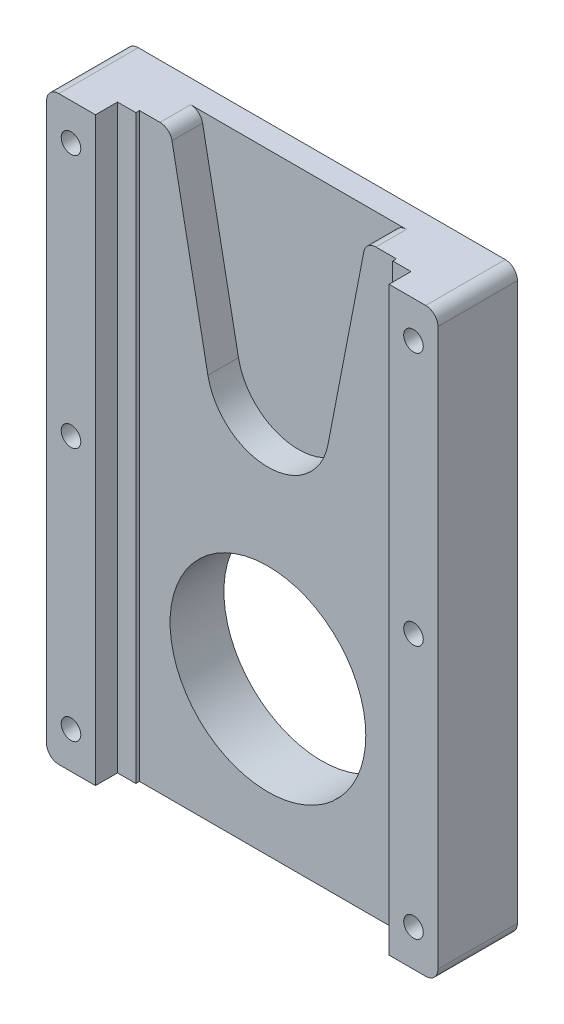
SolidWorks part; units mm, degrees
ref_plane "Plan de face" through (0, 0, 0) normal (0, 0, 1) x (1, 0, 0)
ref_plane "Plan de dessus" through (0, 0, 0) normal (0, 1, 0) x (1, 0, 0)
ref_plane "Plan de droite" through (0, 0, 0) normal (1, 0, 0) x (0, 0, -1)
sketch "Esquisse1" plane through (0, 0, 0) normal (0, 0, 1) x (1, 0, 0)
  line L0 (0, 70) -> (0, 0) construction
  line L1 (-32, 70) -> (32, 70)
  line L2 (-32, 70) -> (-32, -25)
  line L3 (-32, -25) -> (32, -25)
  line L4 (32, 70) -> (32, -25)
  circle A0 centre (0, 0) radius 16
  dimension "D1" = 32
  dimension "D2" = 64
  dimension "D3" = 25
  dimension "D4" = 70
extrude "Boss.-Extru.1" add sketch "Esquisse1" against normal blind 12
sketch "Esquisse2" plane through (0, 0, 0) normal (0, 0, 1) x (1, 0, 0)
  line L0 (32, 70) -> (-32, 70) construction
  line L1 (-24, 70) -> (24, 70)
  line L2 (-24, 70) -> (-24, -25)
  line L3 (-24, -25) -> (24, -25)
  line L4 (24, 70) -> (24, -25)
  line L5 (-32, -25) -> (32, -25) construction
  line L6 (0, 0) -> (0, -25) construction
  dimension "D1" = 48
extrude "Enlèv. mat.-Extru.1" cut sketch "Esquisse2" against normal blind 2.6
sketch "Esquisse3" plane through (0, 0, -2.6) normal (0, 0, 1) x (1, 0, 0)
  line L0 (24, 70) -> (-24, 70) construction
  line L1 (-21, 70) -> (21, 70)
  line L2 (-21, 70) -> (-21, -25)
  line L3 (-21, -25) -> (21, -25)
  line L4 (21, 70) -> (21, -25)
  line L5 (-24, -25) -> (24, -25) construction
  line L6 (0, 0) -> (0, -25) construction
  dimension "D1" = 42
extrude "Enlèv. mat.-Extru.2" cut sketch "Esquisse3" against normal blind 0.6
sketch "Esquisse4" plane through (0, 0, 0) normal (0, 0, 1) x (1, 0, 0)
  line L0 (-28, 22.5) -> (-32, 22.5) construction
  line L1 (-32, 70) -> (-32, -25) construction
  line L2 (-28, 70) -> (-28, -25) construction
  line L3 (-24, 70) -> (-32, 70) construction
  line L4 (-32, -25) -> (-24, -25) construction
  circle A0 centre (-28, -19) radius 1.6
  circle A1 centre (-28, 22.5) radius 1.6
  circle A2 centre (-28, 64) radius 1.6
  dimension "D1" = 3.2
  dimension "D2" = 6
extrude "Enlèv. mat.-Extru.4" cut sketch "Esquisse4" against normal through all
mirror "Symétrie1" about plane through (0, 0, 0) normal (1, 0, 0) of "Enlèv. mat.-Extru.4"
sketch "Esquisse5" plane through (0, 0, -3.2) normal (0, 0, 1) x (1, 0, 0)
  line L0 (0, 70) -> (0, 40) construction
  line L1 (21, 70) -> (-21, 70) construction
  line L2 (-21, -25) -> (21, -25) construction
  line L3 (16, 70) -> (9.8173, 38.0974)
  line L4 (-9.8173, 38.0974) -> (-16, 70)
  line L5 (-16, 70) -> (16, 70)
  arc A0 (-9.8173, 38.0974) -> (9.8173, 38.0974) centre (0, 40) ccw
  dimension "D3" = 10
  dimension "D1" = 65
  dimension "D2" = 32
extrude "Enlèv. mat.-Extru.5" cut sketch "Esquisse5" against normal blind 5
fillet "Congé1" radius 2 6 edges at (32, 70, -6) (32, -25, -6) (-32, -25, -6) (-32, 70, -6) (16, 70, -5.7) (-16, 70, -5.7)
sketch "Esquisse6" plane through (0, 0, 0) normal (0, 0, 1) x (1, 0, 0)
  line L5 (-32, 68) -> (-32, -23)
  line L6 (-30, -25) -> (-24, -25)
  line L7 (-24, -25) -> (-24, 70)
  line L8 (-24, 70) -> (-30, 70)
  line L9 (-32, 68) -> (-32, -23)
  line L10 (-30, -25) -> (-24, -25)
  line L11 (-24, -25) -> (-24, 70)
  line L12 (-24, 70) -> (-30, 70)
  line L13 (32, -23) -> (32, 68)
  line L14 (30, 70) -> (24, 70)
  line L15 (24, 70) -> (24, -25)
  line L16 (24, -25) -> (30, -25)
  line L17 (32, -23) -> (32, 68)
  line L18 (30, 70) -> (24, 70)
  line L19 (24, 70) -> (24, -25)
  line L20 (24, -25) -> (30, -25)
  circle A0 centre (-28, 64) radius 1.6 construction
  circle A1 centre (-28, 22.5) radius 1.6 construction
  arc A2 (-32, -23) -> (-30, -25) centre (-30, -23) ccw
  arc A3 (-30, 70) -> (-32, 68) centre (-30, 68) ccw
  arc A4 (-32, -23) -> (-30, -25) centre (-30, -23) ccw
  arc A5 (-30, 70) -> (-32, 68) centre (-30, 68) ccw
  arc A6 (32, 68) -> (30, 70) centre (30, 68) ccw
  arc A7 (30, -25) -> (32, -23) centre (30, -23) ccw
  arc A8 (32, 68) -> (30, 70) centre (30, 68) ccw
  arc A9 (30, -25) -> (32, -23) centre (30, -23) ccw
  circle A10 centre (-28, -19) radius 1.6 construction
  circle A11 centre (28, -19) radius 1.6 construction
  circle A12 centre (28, 22.5) radius 1.6 construction
  circle A13 centre (28, 64) radius 1.6 construction
  circle A14 centre (-28, 64) radius 1.6
  circle A15 centre (-28, 22.5) radius 1.6
  circle A16 centre (-28, -19) radius 1.6
  circle A17 centre (28, -19) radius 1.6
  circle A18 centre (28, 22.5) radius 1.6
  circle A19 centre (28, 64) radius 1.6
  dimension "D1" = 0
  dimension "D2" = 0
extrude "Boss.-Extru.2" add sketch "Esquisse6" along normal blind 1
